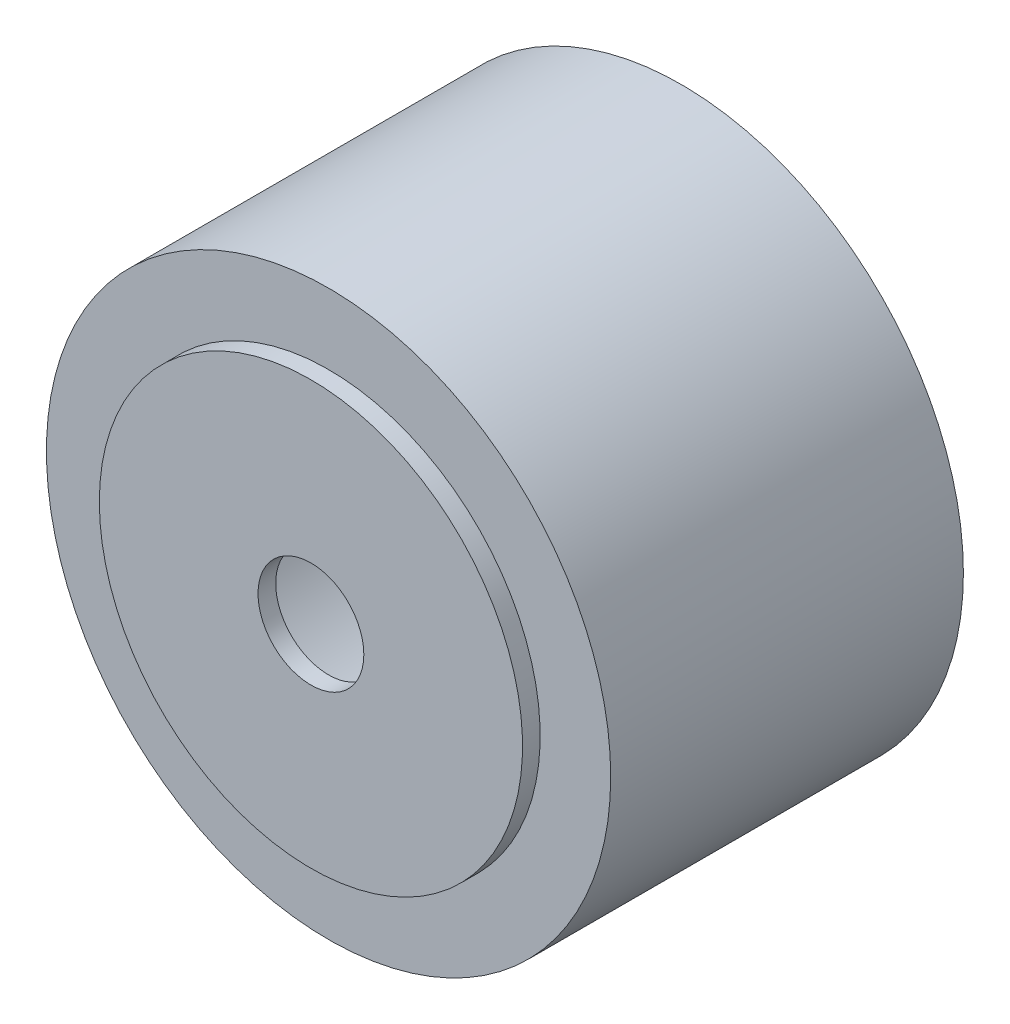
SolidWorks part; units mm, degrees
ref_plane "Plano frontal" through (0, 0, 0) normal (0, 0, 1) x (1, 0, 0)
ref_plane "Plano superior" through (0, 0, 0) normal (0, 1, 0) x (1, 0, 0)
ref_plane "Plano direito" through (0, 0, 0) normal (1, 0, 0) x (0, 0, -1)
sketch "Esboço1" plane through (0, 0, 0) normal (0, 0, 1) x (1, 0, 0)
  circle A0 centre (0, 0) radius 16
  circle A1 centre (0, 0) radius 12
  dimension "D1" = 32
  dimension "D2" = 24
extrude "Ressalto-extrusão1" add sketch "Esboço1" along normal blind 20
sketch "Esboço2" plane through (0, 0, 0) normal (0, 0, -1) x (-1, 0, 0)
  circle A0 centre (0, 0) radius 12
  circle A1 centre (0, 0) radius 10
  dimension "D1" = 20
extrude "Ressalto-extrusão2" add sketch "Esboço2" along normal blind 1 separate body
sketch "Esboço3" plane through (0, 0, 0) normal (0, 0, 1) x (1, 0, 0)
  circle A0 centre (0, 0) radius 10
  circle A1 centre (0, 0) radius 12
extrude "Ressalto-extrusão3" add sketch "Esboço3" along normal blind 21
sketch "Esboço4" plane through (0, 0, 21) normal (0, 0, 1) x (1, 0, 0)
  circle A0 centre (0, 0) radius 10
  circle A1 centre (0, 0) radius 3
  dimension "D1" = 6
extrude "Ressalto-extrusão4" add sketch "Esboço4" against normal blind 1
